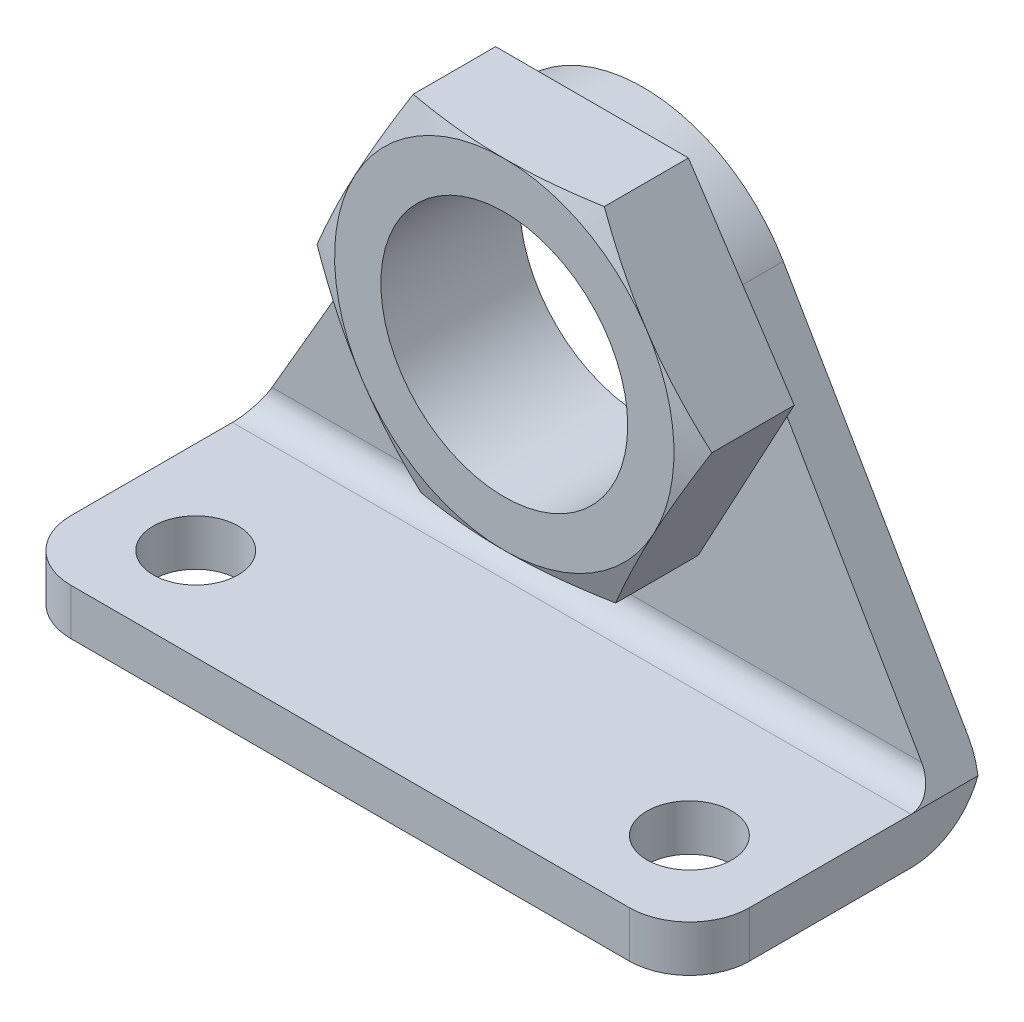
SolidWorks part; units mm, degrees
ref_plane "前视基准面" through (0, 0, 0) normal (0, 0, 1) x (1, 0, 0)
ref_plane "上视基准面" through (0, 0, 0) normal (0, 1, 0) x (1, 0, 0)
ref_plane "右视基准面" through (0, 0, 0) normal (1, 0, 0) x (0, 0, -1)
sketch "草图1" plane through (0, 0, 0) normal (0, 0, 1) x (1, 0, 0)
  line L0 (0, 0) -> (0, 20) construction
  line L1 (-22, 0) -> (22, 0) construction
  circle A0 centre (0, 20) radius 8
  circle A1 centre (0, 20) radius 10.5
  point P5 (16, 0)
  point P6 (0, 3)
  point P9 (0, 30.5)
  dimension "L" = 16
  dimension "U" = 21
  dimension "AE" = 44
  dimension "AF" = 32
  dimension "AH" = 20
  dimension "AT" = 3
sketch "草图2" plane through (0, 0, 0) normal (1, 0, 0) x (0, 0, -1)
  line L0 (0, 0) -> (-13, 0) construction
  line L1 (-13, 0) -> (-13, 3) construction
  point P3 (-10.25, 0)
  point P6 (-19, 0)
  point P7 (-38, 0)
  dimension "AL" = 13
  dimension "AP" = 5.5
  dimension "AQ" = 6
  dimension "AB" = 25
sketch "螺母" plane through (0, 0, 0) normal (0, 0, 1) x (1, 0, 0)
  line L0 (-9.68, 25.2247) -> (9.68, 14.7753) construction
  line L1 (-5.9372, 9) -> (5.9372, 31) construction
  line L2 (-6.5628, 31) -> (-12.7972, 19.4494)
  line L3 (12.7972, 20.5506) -> (6.5628, 9)
  line L4 (5.9372, 31) -> (-6.5628, 31)
  line L5 (5.9372, 31) -> (12.7972, 20.5506)
  line L6 (-5.9372, 9) -> (-12.7972, 19.4494)
  line L7 (-5.9372, 9) -> (6.5628, 9)
  line L8 (0, 20) -> (-5.28, 22.8498) construction
  circle A1 centre (0, 20) radius 11 construction
  dimension "AY" = 22
  dimension "AX" = 25
  dimension "AR" = 6
sketch "草图4" plane through (0, 0, 0) normal (1, 0, 0) x (0, 0, -1)
  line L0 (-19, 0) -> (-4.625, 0)
  line L1 (0, 4.625) -> (0, 30.5)
  line L3 (-19, 0) -> (-19, 3)
  line L4 (-19, 3) -> (-4.625, 3)
  line L5 (-3, 4.625) -> (-3, 30.5)
  line L6 (-3, 30.5) -> (0, 30.5)
  line L7 (0, 30.5) -> (0, 9.5) construction
  arc A0 (-4.625, 3) -> (-3, 4.625) centre (-4.625, 4.625) ccw
  arc A1 (-3, 8.9551) -> (-8.9551, 3) centre (-4.625, 4.625) ccw construction
  arc A2 (-4.625, 0) -> (0, 4.625) centre (-4.625, 4.625) ccw
  dimension "D1" = 3.25
extrude "凸台-拉伸1" add sketch "草图4" along normal up to vertex (22 mm away) from vertex at -22 starting at point (-22, 0, 0)
sketch "草图5" plane through (0, 0, 3) normal (0, 0, 1) x (1, 0, 0)
  line L0 (-9.0825, 25.2686) -> (-22, 3)
  line L1 (9.0825, 25.2686) -> (22, 3)
  line L2 (-22, 3) -> (-22, 31.5)
  line L3 (-22, 31.5) -> (22, 31.5)
  line L4 (22, 31.5) -> (22, 3)
  circle A0 centre (0, 20) radius 10.5 construction
  arc A1 (9.0825, 25.2686) -> (-9.0825, 25.2686) centre (0, 20) ccw
  dimension "D1" = 1
extrude "切除-拉伸1" cut sketch "草图5" against normal blind 10 and the other way up to surface other way up to face at (0, 1.5, 19)
sketch "草图6" plane through (0, 0, 3) normal (0, 0, 1) x (1, 0, 0)
  circle A0 centre (0, 20) radius 8 construction
  circle A1 centre (0, 20) radius 8
extrude "切除-拉伸2" cut sketch "草图6" against normal through all
sketch "草图7" plane through (0, 3, 0) normal (0, 1, 0) x (1, 0, 0)
  line L1 (0, 0) -> (0, -10.25) construction
  circle A0 centre (16, -13) radius 2.75
  circle A1 centre (-16, -13) radius 2.75
  point P2 (16, -10.25)
  point P11 (-16, -10.25)
extrude "切除-拉伸3" cut sketch "草图7" against normal through all
fillet "圆角1" radius 3.9 2 edges at (-22, 1.5, 19) (22, 1.5, 19)
sketch "草图9" plane through (0, 0, 3) normal (0, 0, 1) x (1, 0, 0)
  line L0 (-5.9372, 9) -> (6.5628, 9) construction
  line L1 (12.7972, 20.5506) -> (6.5628, 9) construction
  line L2 (5.9372, 31) -> (12.7972, 20.5506) construction
  line L3 (5.9372, 31) -> (-6.5628, 31) construction
  line L4 (-6.5628, 31) -> (-12.7972, 19.4494) construction
  line L5 (-5.9372, 9) -> (-12.7972, 19.4494) construction
  line L6 (-5.9372, 9) -> (6.5628, 9)
  line L7 (12.7972, 20.5506) -> (6.5628, 9)
  line L8 (5.9372, 31) -> (12.7972, 20.5506)
  line L9 (5.9372, 31) -> (-6.5628, 31)
  line L10 (-6.5628, 31) -> (-12.7972, 19.4494)
  line L11 (-5.9372, 9) -> (-12.7972, 19.4494)
extrude "凸台-拉伸2" add sketch "草图9" along normal blind 6
ref_plane "基准面1" through (0, 0, 0) normal (1, 0, 0) x (0, 0, -1)
sketch "草图10" plane through (0, 0, 0) normal (1, 0, 0) x (0, 0, 1)
  line L3 (9, -31) -> (9, -34.5)
  line L6 (9, -34.5) -> (7.7261, -34.5)
  line L7 (7.7261, -34.5) -> (9, -31)
  dimension "D1" = 20
  dimension "D2" = 3.5
revolve "切除-旋转1" cut sketch "草图10" angle 360 about axis through (0, 20, 71.4238) along (0, 0, -1)
sketch "草图11" plane through (0, 0, 3) normal (0, 0, -1) x (-1, 0, 0)
  circle A1 centre (0, 20) radius 8
  circle A2 centre (0, 20) radius 8
  dimension "D1" = 0
extrude "切除-拉伸4" cut sketch "草图11" against normal through all
equation "\"D1@草图4\" = \"AL@草图2\"*0.25"
equation "\"D1@圆角1\" = \"AL@草图2\"*0.3"
equation "\"D1@凸台-拉伸2\" = \"AR@螺母\""
